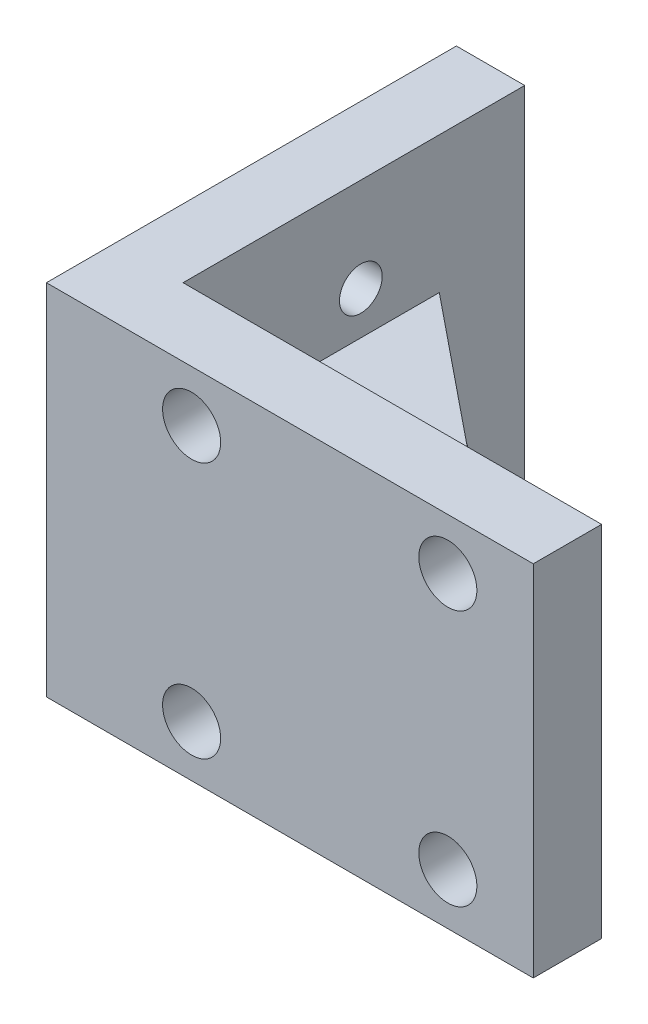
SolidWorks part; units mm, degrees
ref_plane "前视基准面" through (0, 0, 0) normal (0, 0, 1) x (1, 0, 0)
ref_plane "上视基准面" through (0, 0, 0) normal (0, 1, 0) x (1, 0, 0)
ref_plane "右视基准面" through (0, 0, 0) normal (1, 0, 0) x (0, 0, -1)
other "Configuration Table"
sketch "草图1" plane through (0, 0, 0) normal (0, 0, 1) x (1, 0, 0)
  line L1 (0, 0) -> (28.5, 0)
  line L2 (0, 0) -> (0, 21)
  line L3 (0, 21) -> (28.5, 21)
  line L4 (28.5, 0) -> (28.5, 21)
  dimension "D1" = 28.5
  dimension "D2" = 21
extrude "凸台-拉伸1" add sketch "草图1" along normal blind 4
sketch "草图2" plane through (0, 0, 0) normal (0, 0, -1) x (-1, 0, 0)
  line L0 (0, 21) -> (0, 0) construction
  line L1 (0, 0) -> (-4, 0)
  line L2 (0, 0) -> (0, 21)
  line L3 (0, 21) -> (-4, 21)
  line L4 (-4, 0) -> (-4, 21)
  line L5 (-28.5, 21) -> (0, 21) construction
  dimension "D1" = 4
extrude "凸台-拉伸2" add sketch "草图2" along normal blind 20
ref_plane "基准面1" through (0, 10.5, 0) normal (0, -1, 0) x (-1, 0, 0)
sketch "草图3" plane through (0, 10.5, 0) normal (0, -1, 0) x (-1, 0, 0)
  line L0 (-22.5, 0) -> (-4, 15)
  line L1 (-4, 0) -> (-28.5, 0) construction
  line L2 (-4, 20) -> (-4, 0) construction
  line L3 (-4, 20) -> (0, 20) construction
  line L4 (-28.5, -4) -> (-28.5, 0) construction
  dimension "D1" = 5
  dimension "D2" = 6
rib "筋1" sketch "草图3" sketch "草图3" thickness 5 extrusion direction parallel to sketch draft on no parameters "D1"=5
sketch "草图4" plane through (0, 0, 0) normal (-1, 0, 0) x (0, 0, 1)
  circle A0 centre (-2.406, 15.5) radius 1.25
  circle A1 centre (-10.406, 15.5) radius 1.25
  point P4 (-1.406, 15.5)
  point P6 (-9.406, 15.5)
extrude "切除-拉伸1" cut sketch "草图4" against normal up to next
sketch "草图5" plane through (0, 0, 4) normal (0, 0, 1) x (1, 0, 0)
  circle A0 centre (23.5, 18) radius 1.7
  circle A1 centre (8.5, 3) radius 1.7
  circle A2 centre (23.5, 3) radius 1.7
  circle A3 centre (8.5, 18) radius 1.7
extrude "切除-拉伸2" cut sketch "草图5" against normal up to next
sketch "草图6" plane through (4, 0, 0) normal (1, 0, 0) x (0, 0, -1)
  line L0 (20, 21) -> (20, 0) construction
  line L1 (20, 0) -> (0, 0) construction
  line L2 (0, 0) -> (0, 21) construction
  circle A0 centre (5, 4) radius 1.7
  circle A1 centre (15, 4) radius 1.7
  point P4 (15, 15.815)
  dimension "D1" = 3.4
  dimension "D2" = 3.4
  dimension "D5" = 5
  dimension "D6" = 4
  dimension "D3" = 5
  dimension "D4" = 4
extrude "切除-拉伸3" cut sketch "草图6" against normal up to next
